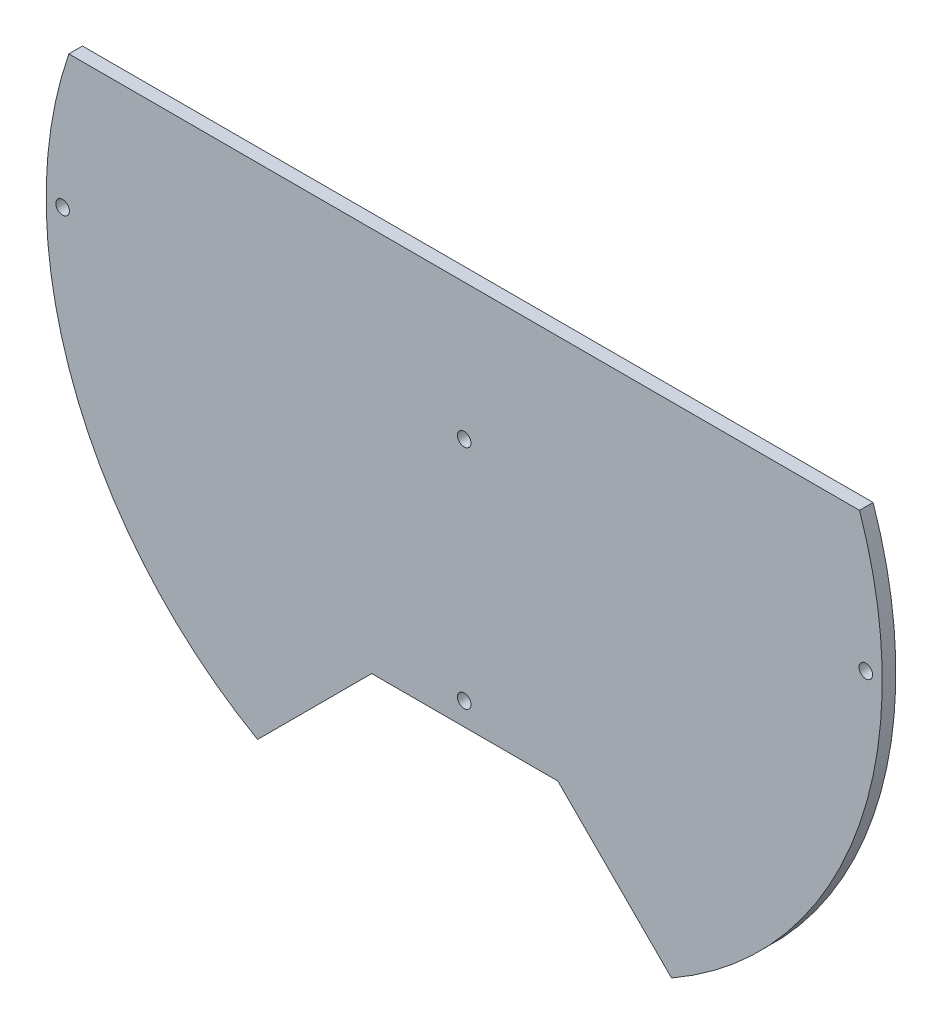
SolidWorks part; units mm, degrees
ref_plane "Alzado" through (0, 0, 0) normal (0, 0, 1) x (1, 0, 0)
ref_plane "Planta" through (0, 0, 0) normal (0, 1, 0) x (1, 0, 0)
ref_plane "Vista lateral" through (0, 0, 0) normal (1, 0, 0) x (0, 0, -1)
sketch "Croquis1" plane through (0, 0, 0) normal (0, 0, 1) x (1, 0, 0)
  line L0 (87.2187, 55.0907) -> (-87.2187, 55.0907)
  line L1 (-20.404, -29.9093) -> (20.6488, -29.9093)
  line L2 (20.6488, -29.9093) -> (45.7415, -55.0019)
  line L3 (-20.404, -29.9093) -> (-45.5855, -55.0907)
  arc A0 (45.7415, -55.0019) -> (87.2187, 55.0907) centre (0, 25.0907) ccw
  arc A1 (-87.2187, 55.0907) -> (-45.5855, -55.0907) centre (0, 25.0907) ccw
  circle A2 centre (0, -24.9093) radius 1.5
  circle A3 centre (88.6057, 25.0907) radius 1.5
  circle A4 centre (0, 25.0907) radius 1.5
  circle A5 centre (-88.6057, 25.0907) radius 1.5
  point P5 (0, 55.0907)
  point P8 (0.1224, -29.9093)
extrude "Saliente-Extruir1" add sketch "Croquis1" along normal blind 3
